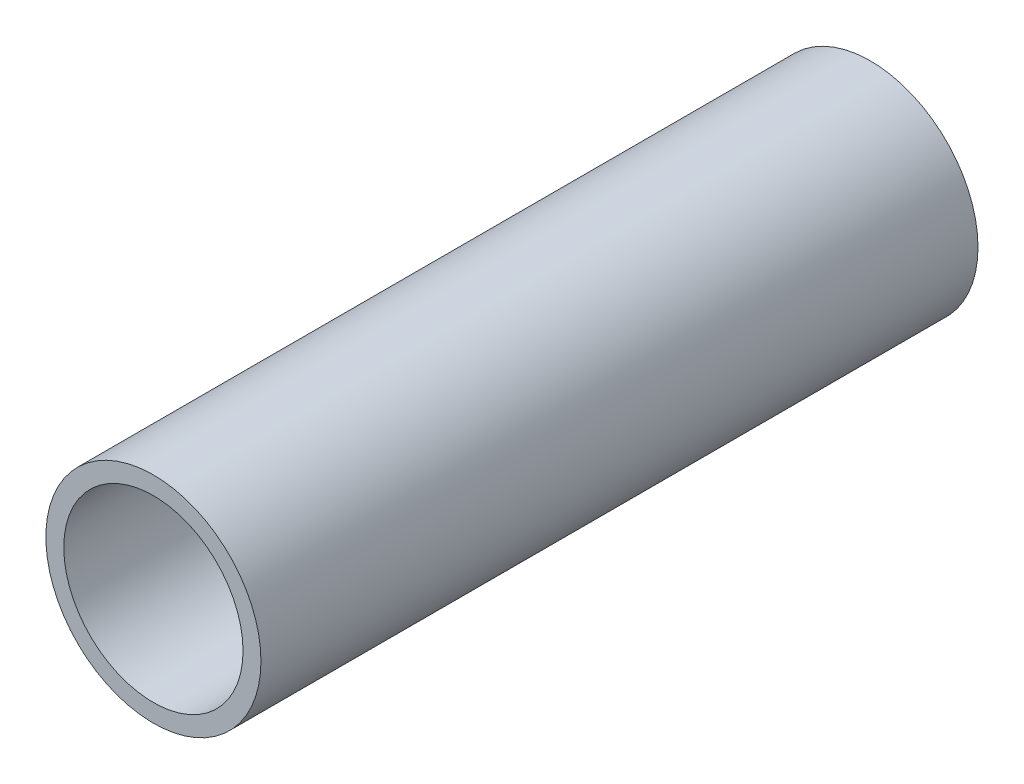
SolidWorks part; units mm, degrees
ref_plane "Front Plane" through (0, 0, 0) normal (0, 0, 1) x (1, 0, 0)
ref_plane "Top Plane" through (0, 0, 0) normal (0, 1, 0) x (1, 0, 0)
ref_plane "Right Plane" through (0, 0, 0) normal (1, 0, 0) x (0, 0, -1)
sketch "Sketch1" plane through (0, 0, 0) normal (0, 0, 1) x (1, 0, 0)
  circle A0 centre (0, 0) radius 15
  circle A1 centre (0, 0) radius 12.5
  dimension "D1" = 25
  dimension "D2" = 30
extrude "Boss-Extrude1" add sketch "Sketch1" along normal blind 100
